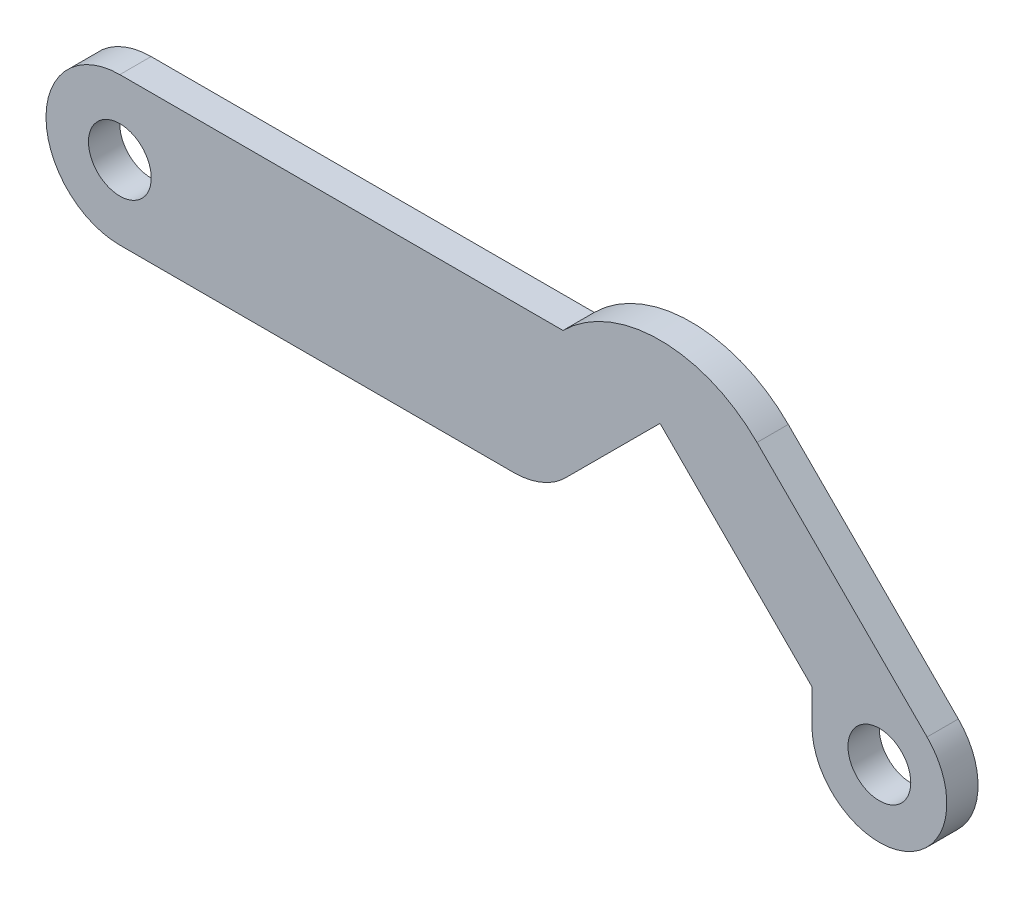
SolidWorks part; units mm, degrees
ref_plane "Front Plane" through (0, 0, 0) normal (0, 0, 1) x (1, 0, 0)
ref_plane "Top Plane" through (0, 0, 0) normal (0, 1, 0) x (1, 0, 0)
ref_plane "Right Plane" through (0, 0, 0) normal (1, 0, 0) x (0, 0, -1)
sketch "Sketch1" plane through (0, 0, 0) normal (0, 0, 1) x (1, 0, 0)
  line L0 (-37.5, 0) -> (37.5, 0)
  line L1 (-37.5, 0) -> (37.5, 0) construction
  line L2 (-37.5, 7.5) -> (37.5, 7.5)
  line L3 (-37.5, -7.5) -> (37.5, -7.5)
  arc A0 (-37.5, 7.5) -> (-37.5, -7.5) centre (-37.5, 0) ccw
  arc A1 (37.5, -7.5) -> (37.5, 7.5) centre (37.5, 0) ccw
  circle A2 centre (-37.5, 0) radius 3.175
  circle A3 centre (37.5, 0) radius 4.8
  point P0 (0, 0)
  point P4 (0, 0)
  dimension "D1" = 6.35
  dimension "D2" = 9.6
  dimension "D3" = 7.5
  dimension "D4" = 75
extrude "Boss-Extrude1" add sketch "Sketch1" along normal blind 3.175
sketch "Sketch2" plane through (0, 0, 3.175) normal (0, 0, 1) x (1, 0, 0)
  line L1 (-25, -1.3705) -> (-10, -1.3705)
  line L2 (-25, -1.3705) -> (-25, 1.8045)
  line L3 (-25, 1.8045) -> (-10, 1.8045)
  line L4 (-10, -1.3705) -> (-10, 1.8045)
  line L5 (-25, -1.3705) -> (-10, 1.8045) construction
  line L6 (-25, 1.8045) -> (-10, -1.3705) construction
  line L7 (10, -0.734) -> (25, -0.734)
  line L8 (10, -0.734) -> (10, 2.441)
  line L9 (10, 2.441) -> (25, 2.441)
  line L10 (25, -0.734) -> (25, 2.441)
  line L11 (10, -0.734) -> (25, 2.441) construction
  line L12 (10, 2.441) -> (25, -0.734) construction
  point P0 (-17.5, 0.217)
  point P5 (17.5, 0.8535)
  dimension "D1" = 3.175
  dimension "D2" = 3.175
  dimension "D3" = 15
  dimension "D4" = 15
  dimension "D5" = 20
  dimension "D6" = 10
extrude "Cut-Extrude1" cut sketch "Sketch2" against normal through all contours L2 L1 L4 L3 | L8 L7 L10 L9
sketch "Sketch3" plane through (0, 0, 3.175) normal (0, 0, 1) x (1, 0, 0)
  line L0 (-37.5, 0) -> (-20.71, 0)
  line L2 (-20.71, 0) -> (-56.5053, 0)
  line L3 (-20.71, 0) -> (-20.71, 17.1285)
  line L4 (-20.71, 17.1285) -> (-56.5053, 17.1285)
  line L5 (-56.5053, 0) -> (-56.5053, 17.1285)
  line L6 (-20.71, 0) -> (-56.5053, 0)
  line L7 (-20.71, 0) -> (-20.71, -10.2398)
  line L8 (-20.71, -10.2398) -> (-56.5053, -10.2398)
  line L9 (-56.5053, 0) -> (-56.5053, -10.2398)
  circle M3 centre (-37.5, 0) radius 3.175
  line M4 (-37.5, -7.5) -> (37.5, -7.5)
  line M6 (37.5, 7.5) -> (-37.5, 7.5)
  arc M7 (-37.5, 7.5) -> (-37.5, -7.5) centre (-37.5, 0) ccw
  line M12 (-25, -1.3705) -> (-25, 1.8045)
  line M13 (-25, 1.8045) -> (-10, 1.8045)
  line M15 (-10, -1.3705) -> (-25, -1.3705)
  dimension "D1" = 16.79
extrude "Cut-Extrude2" cut sketch "Sketch3" against normal blind 10 contours L5 L2 L3 L4 M7 M6 | L2 L9 L8 L7 M4 M7 | L3 L2 L0 M13 M6 M7 M3 M12 | L7 L0 L2 M15 M12 M3 M7 M4
sketch "Sketch4" plane through (0, 0, 3.175) normal (0, 0, 1) x (1, 0, 0)
  line L0 (-20.71, 1.8045) -> (-20.71, 7.5) construction
  line L1 (-20.71, 2.6568) -> (-9.1283, 2.6568)
  line L2 (-20.71, 2.6568) -> (-20.71, -2.9164)
  line L3 (-20.71, -2.9164) -> (-9.1283, -2.9164)
  line L4 (-9.1283, 2.6568) -> (-9.1283, -2.9164)
extrude "Boss-Extrude2" add sketch "Sketch4" against normal up to surface (3.175 mm away) up to face at (42.3, 0, 0)
sketch "Sketch5" plane through (0, 0, 3.175) normal (0, 0, 1) x (1, 0, 0)
  line L0 (-20.71, 7.5) -> (-20.71, -7.5) construction
  circle A0 centre (-13.5, 0) radius 1.475
  circle A1 centre (2.5, 0) radius 1.475
  dimension "D1" = 7.21
  dimension "D2" = 2.95
  dimension "D3" = 2.95
  dimension "D4" = 16
extrude "Cut-Extrude3" cut sketch "Sketch5" against normal blind 16
sketch "Sketch6" plane through (0, 0, 3.175) normal (0, 0, 1) x (1, 0, 0)
  line L1 (8.271, 4.3719) -> (29.5442, 4.3719)
  line L2 (8.271, 4.3719) -> (8.271, -3.0364)
  line L3 (8.271, -3.0364) -> (29.5442, -3.0364)
  line L4 (29.5442, 4.3719) -> (29.5442, -3.0364)
extrude "Boss-Extrude4" add sketch "Sketch6" against normal up to surface (3.175 mm away) up to face at (-12.025, 0, 0)
sketch "Sketch12" plane through (0, 0, 0) normal (0, 0, -1) x (-1, 0, 0)
  line L0 (-37.5, 7.5) -> (-2.5, 7.5)
  line L1 (-37.5, -7.5) -> (-2.5, -7.5)
  line L2 (20.71, -7.5) -> (20.71, 7.5) construction
  circle A0 centre (-2.5, 0) radius 7.5
  circle A1 centre (-2.5, 0) radius 1.475
  circle A2 centre (-37.5, 0) radius 7.5
  line M6 (20.71, 7.5) -> (-37.5, 7.5)
  arc M7 (-37.5, 7.5) -> (-37.5, -7.5) centre (-37.5, 0) ccw
  line M8 (-37.5, -7.5) -> (20.71, -7.5)
  circle M9 centre (-37.5, 0) radius 4.8
  dimension "D1" = 23.21
extrude "Cut-Extrude5" cut sketch "Sketch12" against normal blind 10 contours A2 A0 M8 M6 | A2 M7 M9
sketch "Sketch15" plane through (0, 0, 0) normal (0, 0, -1) x (-1, 0, 0)
  line L0 (-2.5, 7.5) -> (-43.314, -11.453)
  line L1 (-43.314, -11.453) -> (-35.9577, -17.7755)
  line L2 (-35.9577, -17.7755) -> (-2.5, -7.5)
  line L3 (-2.5, -7.5) -> (-2.5, 7.5)
  line L4 (-46.4858, -14.6142) -> (-39.6358, -21.4642)
  line L5 (-39.6358, -21.4642) -> (-43.0608, -18.0392)
  line L6 (-43.0608, -18.0392) -> (-47.4618, -22.4401)
  line L7 (-43.0608, -18.0392) -> (-32.0312, -7.0096)
  line L8 (-11.7911, 3.1854) -> (-8.23, 4.8391)
  circle A0 centre (-39.6358, -14.6142) radius 4.85
  circle A2 centre (-39.6358, -14.6142) radius 6.85
  arc A3 (-44.4795, -19.4579) -> (-2.5, 7.5) centre (-24.3855, -4.5841) cw
  circle A4 centre (-2.5, 0) radius 7.5
  arc A5 (-34.7398, -9.7182) -> (-10, 0) centre (-22.3699, -4.8591) cw
  arc A6 (-2.5, 7.5) -> (-2.5, -7.5) centre (-2.5, 0) ccw construction
  arc A7 (-10, 0) -> (-8.23, 4.8391) centre (-2.5, 0) cw
  arc A8 (-10, 0) -> (-11.7911, 3.1854) centre (-22.3699, -4.8591) ccw
  dimension "D5" = 25
  dimension "D6" = 13.2901
  dimension "D1" = 45
  dimension "D2" = 9.7
  dimension "D3" = 35
  dimension "D4" = 2
extrude "Boss-Extrude10" add sketch "Sketch15" against normal up to surface (3.175 mm away)
sketch "Sketch16" plane through (0, 0, 0) normal (0, 0, -1) x (-1, 0, 0)
  line L0 (-7.8033, -5.3033) -> (-21.5097, 8.4031)
  arc A0 (-10, 0) -> (-2.5, -7.5) centre (-2.5, 0) ccw construction
  arc A1 (-10, 0) -> (-34.7398, -9.7182) centre (-22.3699, -4.8591) ccw construction
  circle A2 centre (-14.6565, 1.5499) radius 9.6919
  arc M7 (-34.7398, -9.7182) -> (-10, 0) centre (-22.3699, -4.8591) cw
  arc M8 (-10, 0) -> (-2.5, -7.5) centre (-2.5, 0) ccw
extrude "Boss-Extrude11" add sketch "Sketch16" against normal up to surface (3.175 mm away) contours L0 M8 M7 up to face at (3.975, 0, 3.175)
sketch "Sketch17" plane through (0, 0, 0) normal (0, 0, -1) x (-1, 0, 0)
  line L0 (-34.7922, -9.7705) -> (-34.7398, -9.7182)
  line L1 (-34.7922, -9.7705) -> (-32.9259, -7.9042)
  line L2 (-34.7922, -9.7705) -> (-19.0641, 5.9575)
  line L3 (-7.8033, -5.3033) -> (-21.5097, 8.4031) construction
  line L4 (-19.0641, 5.9575) -> (-20.7559, 9.5193)
  line L5 (-20.7559, 9.5193) -> (-23.454, 8.6584)
  circle A1 centre (-26.9281, -1.9065) radius 11.1214
  line M2 (-21.5097, 8.4031) -> (-7.8033, -5.3033)
  line M9 (-34.7922, -9.7705) -> (-34.7398, -9.7182)
  arc M10 (-34.7398, -9.7182) -> (-21.5097, 8.4031) centre (-22.3699, -4.8591) cw
extrude "Boss-Extrude12" add sketch "Sketch17" against normal up to surface (3.175 mm away) contours A1 L4 L5 M10 M2 | A1 M2 M10 | L2 A1 L1 M10 | A1 M10 M9 up to face at (13.5062, -1.7017, 3.175)
sketch "Sketch18" plane through (0, 0, 0) normal (0, 0, -1) x (-1, 0, 0)
  line L0 (-49.3855, -4.5841) -> (-24.3855, 20.4159)
  line L1 (-49.3855, -4.5841) -> (-55.4039, 2.1365)
  line L2 (-55.4039, 2.1365) -> (-30.5677, 24.378)
  line L3 (-30.5677, 24.378) -> (-24.3855, 20.4159)
  arc A0 (-2.5, 7.5) -> (-46.0019, -17.1431) centre (-24.3855, -4.5841) ccw construction
extrude "Cut-Extrude6" cut sketch "Sketch18" against normal blind 10
sketch "Sketch19" plane through (0, 0, 0) normal (0, 0, -1) x (-1, 0, 0)
  line L0 (-39.6358, -14.6142) -> (-44.4795, -9.7705)
  line L1 (-44.4795, -9.7705) -> (-15.8099, 18.8991)
  line L2 (-45.042, -18.8208) -> (-55.9249, -16.9199)
  line L3 (-55.9249, -16.9199) -> (-55.2634, -4.1714)
  line L4 (-55.2634, -4.1714) -> (-13.4876, 33.4823)
  line L5 (-13.4876, 33.4823) -> (-15.8099, 18.8991)
  circle A0 centre (-39.6358, -14.6142) radius 6.85
  arc A1 (-2.5, 7.5) -> (-24.3855, 20.4159) centre (-24.3855, -4.5841) ccw construction
  arc M2 (-2.5, 7.5) -> (-24.3855, 20.4159) centre (-24.3855, -4.5841) ccw
  line M3 (-24.3855, 20.4159) -> (-49.3855, -4.5841)
  arc M4 (-49.3855, -4.5841) -> (-46.0019, -17.1431) centre (-24.3855, -4.5841) ccw
extrude "Cut-Extrude7" cut sketch "Sketch19" against normal blind 10 contours A0 L1 M2 M3 M4
sketch "Sketch20" plane through (0, 0, 0) normal (0, 0, -1) x (-1, 0, 0)
  line L0 (-32.7858, -14.6142) -> (-32.7858, -7.7642)
  line L1 (-34.7922, -9.7705) -> (-19.0641, 5.9575) construction
  line L2 (-46.4858, -14.6142) -> (-46.4858, -7.7642)
  line L3 (-46.4858, -7.7642) -> (-15.8099, 18.8991)
  line L4 (-46.4858, -14.6142) -> (-15.8099, 18.8991)
  line L5 (-35.5858, -9.4177) -> (-32.7858, -14.6142)
  arc A0 (-44.4795, -9.7705) -> (-34.7922, -9.7705) centre (-39.6358, -14.6142) ccw construction
  arc A1 (-32.7858, -7.7642) -> (-35.5858, -9.4177) centre (-32.7858, -10.9617) ccw
extrude "Boss-Extrude13" add sketch "Sketch20" against normal up to surface (3.175 mm away) contours L4 L3 L2 | L5 L0 A1 up to face at (3.975, 0, 3.175)
sketch "Sketch21" plane through (0, 0, 0) normal (0, 0, -1) x (-1, 0, 0)
  line L0 (-15.8099, 18.8991) -> (-3.4947, 5.1883)
  line L1 (-3.4947, 5.1883) -> (20.71, 7.5)
  arc A0 (20.71, 7.5) -> (-15.8099, 18.8991) centre (-12.3346, -34.1671) ccw
extrude "Boss-Extrude14" add sketch "Sketch21" against normal up to surface (3.175 mm away) up to face at (14.908, -2.8524, 3.175)
sketch "Sketch22" plane through (0, 0, 0) normal (0, 0, -1) x (-1, 0, 0)
  line L0 (-2.5, 7.5) -> (-19.0641, 5.9575)
  line L1 (-19.0641, 5.9575) -> (-7.8033, -5.3033)
  circle A0 centre (-2.5, 0) radius 7.5
  line M7 (-19.0641, 5.9575) -> (-7.8033, -5.3033)
extrude "Cut-Extrude8" cut sketch "Sketch22" against normal blind 10 contours A0 L0 M7
sketch "Sketch8" plane through (0, 0, 3.175) normal (0, 0, 1) x (1, 0, 0)
  line L1 (14, -1.5875) -> (24, -1.5875)
  line L2 (14, -1.5875) -> (14, 1.5875)
  line L3 (14, 1.5875) -> (24, 1.5875)
  line L4 (24, -1.5875) -> (24, 1.5875)
  line L5 (14, -1.5875) -> (24, 1.5875) construction
  line L6 (14, 1.5875) -> (24, -1.5875) construction
  point P0 (19, 0)
  dimension "D1" = 14
  dimension "D2" = 3.175
  dimension "D3" = 1.5875
  dimension "D4" = 10
extrude "Cut-Extrude4" cut sketch "Sketch8" against normal blind 10
sketch "Sketch24" plane through (0, 0, 0) normal (0, 0, -1) x (-1, 0, 0)
  line L0 (-32.7858, -7.7642) -> (-19.0641, 5.9575)
  line L1 (-19.0641, 5.9575) -> (-25.925, 1.8358)
  line L2 (-25.925, 1.8358) -> (-32.7858, -7.7642)
extrude "Boss-Extrude15" add sketch "Sketch24" against normal up to surface (3.175 mm away) up to face at (18.1178, -1.532, 3.175)
sketch "Sketch25" plane through (0, 0, 0) normal (0, 0, -1) x (-1, 0, 0)
  line L0 (-39.6358, -9.7642) -> (-44.4858, -14.6142)
  line L1 (-44.4858, -14.6142) -> (-42.0608, -12.1892)
  line L2 (-42.0608, -12.1892) -> (-49.4465, -4.8036)
  line L3 (-39.6358, -9.7642) -> (-44.4795, -9.7705)
  line L4 (-42.0608, -9.3608) -> (-42.0608, -9.3608)
  line L5 (-44.4795, -9.7705) -> (-15.8099, 18.8991)
  line L6 (-42.0608, -9.3608) -> (-48.0323, -3.3894) construction
  line L7 (-41.0501, -8.35) -> (-42.0608, -9.3608) construction
  line L8 (-15.8099, 18.8991) -> (-62.9613, 8.7112)
  line L9 (-62.9613, 8.7112) -> (-46.4858, -14.6142)
  circle A0 centre (-39.6358, -14.6142) radius 4.85
  circle A1 centre (-39.6358, -14.6142) radius 6.85
  dimension "D1" = 2
extrude "Cut-Extrude10" cut sketch "Sketch25" against normal blind 10
sketch "Sketch26" plane through (0, 0, 0) normal (0, 0, -1) x (-1, 0, 0)
  line L0 (-19.0641, 5.9575) -> (-23.9078, 10.8012)
  line L1 (-44.4795, -9.7705) -> (-15.8099, 18.8991) construction
  line L2 (-23.9078, 10.8012) -> (-24.4629, 21.1534)
  line L3 (-24.4629, 21.1534) -> (12.5105, 32.5108)
  line L4 (12.5105, 32.5108) -> (20.5457, 7.6298)
  arc A0 (-23.9078, 10.8012) -> (20.5457, 7.6298) centre (-4.4631, -29.7809) cw
  arc A1 (20.71, 7.5) -> (-15.8099, 18.8991) centre (-12.3346, -34.1671) ccw construction
  arc M1 (20.71, 7.5) -> (-15.8099, 18.8991) centre (-12.3346, -34.1671) ccw
  line M2 (-15.8099, 18.8991) -> (-44.4795, -9.7705)
  dimension "D1" = 45
extrude "Cut-Extrude11" cut sketch "Sketch26" against normal blind 10 contours A0 M2 M1 | L4 L3 L2 M2 M1
sketch "Sketch27" plane through (0, 0, 0) normal (0, 0, -1) x (-1, 0, 0)
  line L0 (-9.9677, -0.6954) -> (-2.5, -7.5)
  line L1 (-2.5, -7.5) -> (-6.2338, -4.0977)
  line L2 (-6.2338, -4.0977) -> (-9.9677, -8.1954)
  line L3 (-2.5, -7.5) -> (-7.5515, -5.5437)
  line L4 (-7.5515, -5.5437) -> (-19.0641, 5.9575)
  line L5 (-19.0641, 5.9575) -> (-2.5, 9.0718)
  line L6 (-2.5, 9.0718) -> (-4.8631, 2.7586)
  line L7 (-4.8631, 2.7586) -> (-9.9677, -0.6954)
  arc A0 (-3.8848, 7.371) -> (-2.5, -7.5) centre (-2.5, 0) ccw construction
  line M10 (-19.0641, 5.9575) -> (-3.8848, 7.371)
  arc M11 (-3.8848, 7.371) -> (-2.5, -7.5) centre (-2.5, 0) ccw
extrude "Boss-Extrude16" add sketch "Sketch27" against normal up to surface (3.175 mm away) contours L4 M11 M10 up to face at (44.4858, -14.6142, 3.175)
sketch "Sketch28" plane through (0, 0, 0) normal (0, 0, -1) x (-1, 0, 0)
  line L0 (20.71, 7.5) -> (-23.9078, 10.8012)
  line L1 (-23.9078, 10.8012) -> (-10.7304, 19.8986)
  line L2 (-10.7304, 19.8986) -> (15.1582, 17.0435)
  line L3 (15.1582, 17.0435) -> (20.71, 7.5)
extrude "Cut-Extrude12" cut sketch "Sketch28" against normal up to surface (3.175 mm away) up to face at (10.5058, -2.3762, 3.175)
sketch "Sketch29" plane through (0, 0, 0) normal (0, 0, -1) x (-1, 0, 0)
  line L0 (-19.0641, 5.9575) -> (-32.7858, -7.7642)
  line L1 (-32.7858, -7.7642) -> (-32.7858, -11.1892)
  line L2 (-32.7858, -14.6142) -> (-32.7858, -7.7642) construction
  line L3 (-32.7858, -11.1892) -> (-17.3584, 4.2535)
  line L4 (-8.0387, -5.057) -> (-19.0641, 5.9575) construction
  line L5 (-17.3584, 4.2535) -> (-19.0641, 5.9575)
extrude "Boss-Extrude18" add sketch "Sketch29" against normal up to surface (3.175 mm away) up to face at (14.0026, -4.1424, 3.175)
sketch "Sketch30" plane through (0, 0, 0) normal (0, 0, -1) x (-1, 0, 0)
  line L0 (20.71, 7.5) -> (-29.7262, 7.5)
  line L1 (-29.7262, 7.5) -> (-24.0206, 17.421)
  line L2 (-24.0206, 17.421) -> (20.71, 7.5)
extrude "Cut-Extrude13" cut sketch "Sketch30" against normal up to surface (3.175 mm away) contours L2 L0 L1 up to face at (13.8131, -4.7122, 3.175)
sketch "Sketch31" plane through (0, 0, 0) normal (0, 0, -1) x (-1, 0, 0)
  line L0 (20.71, 7.5) -> (-27.209, 7.5) construction
  line L1 (-27.209, 7.5) -> (-7.5079, 7.5)
  arc A1 (-27.209, 7.5) -> (-7.5079, 7.5) centre (-17.3584, -2.3506) cw
extrude "Boss-Extrude19" add sketch "Sketch31" against normal up to surface (3.175 mm away) up to face at (44.4858, -14.6142, 3.175)
sketch "Sketch32" plane through (0, 0, 0) normal (0, 0, -1) x (-1, 0, 0)
  circle A0 centre (-39.6358, -14.6142) radius 3.1875
  circle A1 centre (-39.6358, -14.6142) radius 6.7162
  dimension "D1" = 6.375
extrude "Boss-Extrude20" add sketch "Sketch32" against normal up to surface (3.175 mm away) up to face at (44.4858, -14.6142, 3.175)
sketch "Sketch33" plane through (0, 0, 0) normal (0, 0, -1) x (-1, 0, 0)
  line L0 (20.71, -7.5) -> (20.71, 7.5) construction
  line L1 (37.5, 7.5) -> (20.71, 7.5)
  line L2 (20.71, -7.5) -> (37.5, -7.5)
  circle A0 centre (37.5, 0) radius 3.1875
  circle A2 centre (37.5, 0) radius 7.5
  line M12 (20.71, -7.5) -> (20.71, 7.5)
  dimension "D1" = 6.375
  dimension "D2" = 16.79
extrude "Boss-Extrude21" add sketch "Sketch33" against normal up to surface (3.175 mm away) contours A2 A0 | A2 L1 L2 M12 up to face at (-12.025, 0, 3.175)
sketch "Sketch34" plane through (0, 0, 0) normal (0, 0, -1) x (-1, 0, 0)
  line L0 (-7.6589, 0.5667) -> (2.6347, -5.6256)
  line L1 (2.6347, -5.6256) -> (22.4177, -2.5294)
  line L2 (22.4177, -2.5294) -> (20.166, 3.9443)
  line L3 (20.166, 3.9443) -> (-4.1205, 3.9443)
  line L4 (-4.1205, 3.9443) -> (-7.6589, 0.5667)
extrude "Boss-Extrude22" add sketch "Sketch34" against normal up to surface (3.175 mm away) up to face at (-12.025, 0, 3.175)
